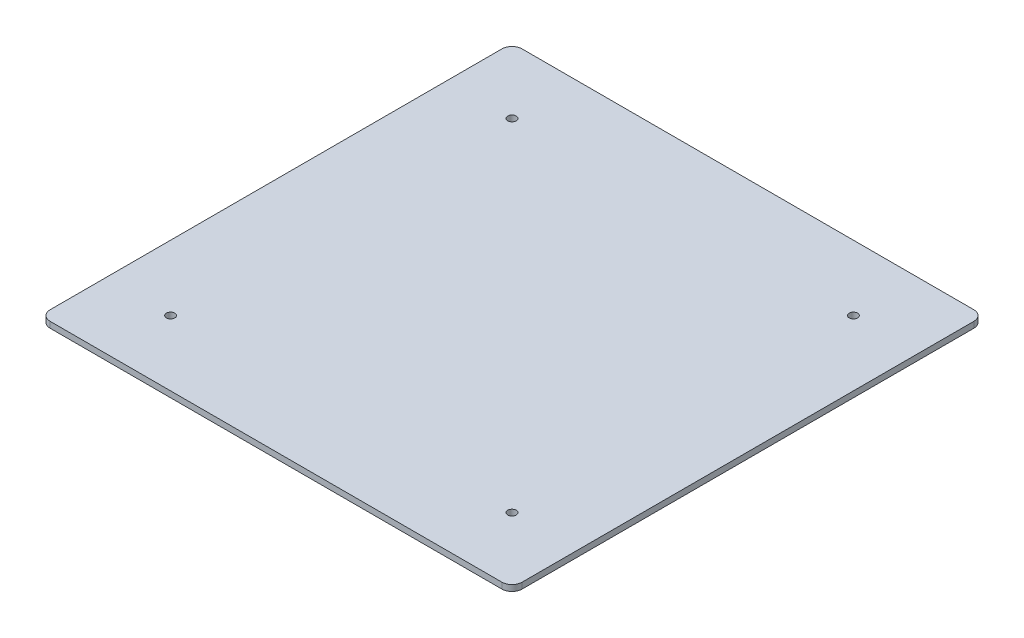
SolidWorks part; units mm, degrees
ref_plane "Front Plane" through (0, 0, 0) normal (0, 0, 1) x (1, 0, 0)
ref_plane "Top Plane" through (0, 0, 0) normal (0, 1, 0) x (1, 0, 0)
ref_plane "Right Plane" through (0, 0, 0) normal (1, 0, 0) x (0, 0, -1)
sketch "Sketch1" plane through (0, 0, 0) normal (0, 1, 0) x (1, 0, 0)
  line L5 (-117.5, 117.5) -> (117.5, -117.5)
  line L6 (-117.5, -117.5) -> (117.5, -117.5)
  line L7 (-117.5, -117.5) -> (-117.5, 117.5)
  line L8 (-117.5, 117.5) -> (117.5, 117.5)
  line L9 (117.5, -117.5) -> (117.5, 117.5)
  line L10 (0, 0) -> (0, 155.1648)
  line L11 (0, 0) -> (-148.5142, -85.7447)
  line L12 (0, 0) -> (152.0297, -87.7744)
  point P12 (0, 0)
  dimension "D5" = 235
  dimension "D6" = 235
  dimension "D7" = 120
  dimension "D8" = 120
extrude "Boss-Extrude1" add sketch "Sketch1" along normal blind 3 contours L11 L5 L7 | L5 L10 L8 | L10 L12 L9 L8 | L12 L5 L9 | L5 L11 L7 L6
sketch "Sketch2" plane through (0, 0, 0) normal (0, -1, 0) x (1, 0, 0)
  line L1 (85, -85) -> (-85, -85) construction
  line L2 (85, -85) -> (85, 85) construction
  line L3 (85, 85) -> (-85, 85) construction
  line L4 (-85, -85) -> (-85, 85) construction
  line L5 (85, -85) -> (-85, 85) construction
  line L6 (85, 85) -> (-85, -85) construction
  circle A0 centre (85, -85) radius 2.1
  circle A1 centre (-85, -85) radius 2.1
  circle A2 centre (-85, 85) radius 2.1
  circle A3 centre (85, 85) radius 2.1
  point P0 (0, 0)
  dimension "D3" = 4.2
  dimension "D1" = 170
  dimension "D2" = 170
extrude "Cut-Extrude1" cut sketch "Sketch2" against normal blind 3 contours A0 | A2 | A3 | A1
fillet "Fillet1" radius 5 4 edges at (-117.5, 1.5, 117.5) (-117.5, 1.5, -117.5) (117.5, 1.5, -117.5) (117.5, 1.5, 117.5)
